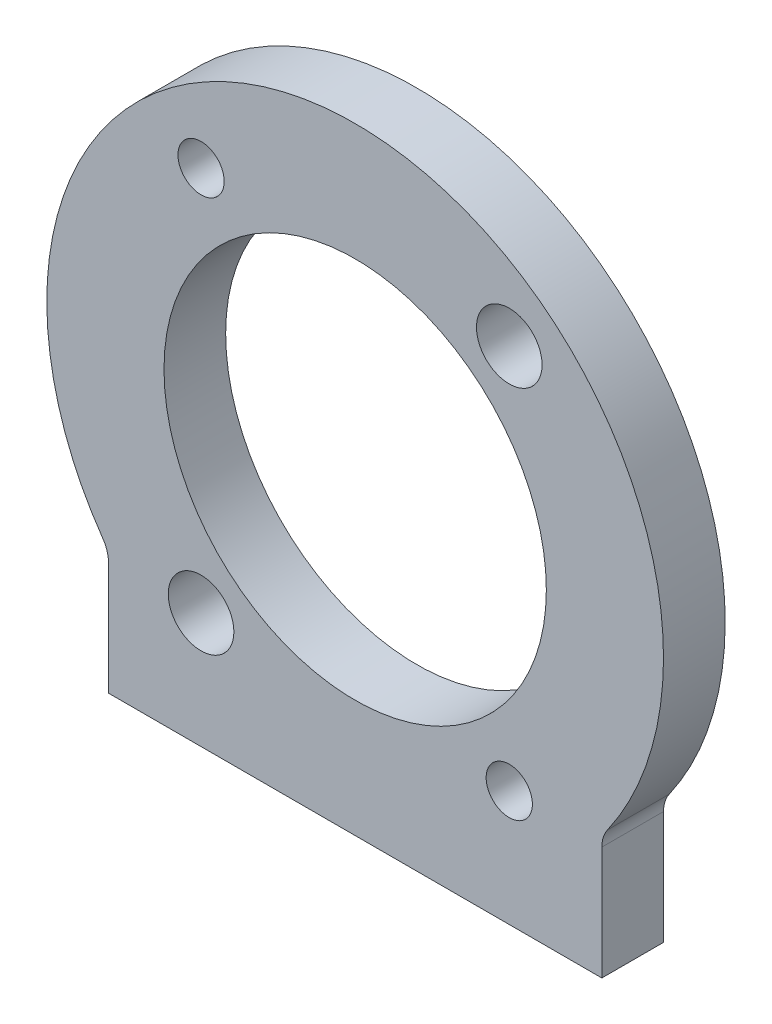
SolidWorks part; units mm, degrees
material "6061 Alloy"
ref_plane "Front" through (0, 0, 0) normal (0, 0, 1) x (1, 0, 0)
ref_plane "Top" through (0, 0, 0) normal (0, 1, 0) x (1, 0, 0)
ref_plane "Right" through (0, 0, 0) normal (1, 0, 0) x (0, 0, -1)
sketch "Sketch1" plane through (0, 0, 0) normal (0, 0, 1) x (1, 0, 0)
  line L0 (-50.8, 63.5) -> (0, 0) construction
  line L1 (0, 0) -> (-50.8, 0)
  line L2 (0, 0) -> (0, 11.6695)
  line L3 (0, 63.5) -> (-50.8, 63.5) construction
  line L4 (-50.8, 0) -> (-50.8, 11.6695)
  line L5 (0, 63.5) -> (-50.8, 0) construction
  line L6 (0, 50.8) -> (0, 63.5) construction
  line L7 (-50.8, 50.8) -> (-50.8, 63.5) construction
  circle A0 centre (-25.4, 31.75) radius 19.685
  circle A2 centre (-25.4, 31.75) radius 25.4 construction
  circle A4 centre (-41.2673, 51.5841) radius 2.3812
  circle A5 centre (-9.5327, 51.5841) radius 3.3782
  circle A6 centre (-9.5327, 11.9159) radius 2.3813
  circle A7 centre (-41.2673, 11.9159) radius 3.3782
  arc A9 (0.5773, 13.495) -> (-51.3773, 13.495) centre (-25.4, 31.75) ccw
  arc A10 (0, 11.6695) -> (0.5773, 13.495) centre (3.175, 11.6695) cw
  arc A11 (-50.8, 11.6695) -> (-51.3773, 13.495) centre (-53.975, 11.6695) ccw
  point P20 (0, 0)
  point P21 (0, 0)
  point P22 (-50.8, 10.7981)
  point P23 (-50.8, 12.7)
  point P24 (0, 12.7)
  dimension "D2" = 39.37
  dimension "D4" = 50.8
  dimension "D5" = 4.7625
  dimension "D6" = 6.7564
  dimension "D7" = 31.75
  dimension "D8" = 3.175
  dimension "D1" = 50.8
  dimension "D3" = 31.75
extrude "Boss-Extrude1" add sketch "Sketch1" along normal blind 6.35
